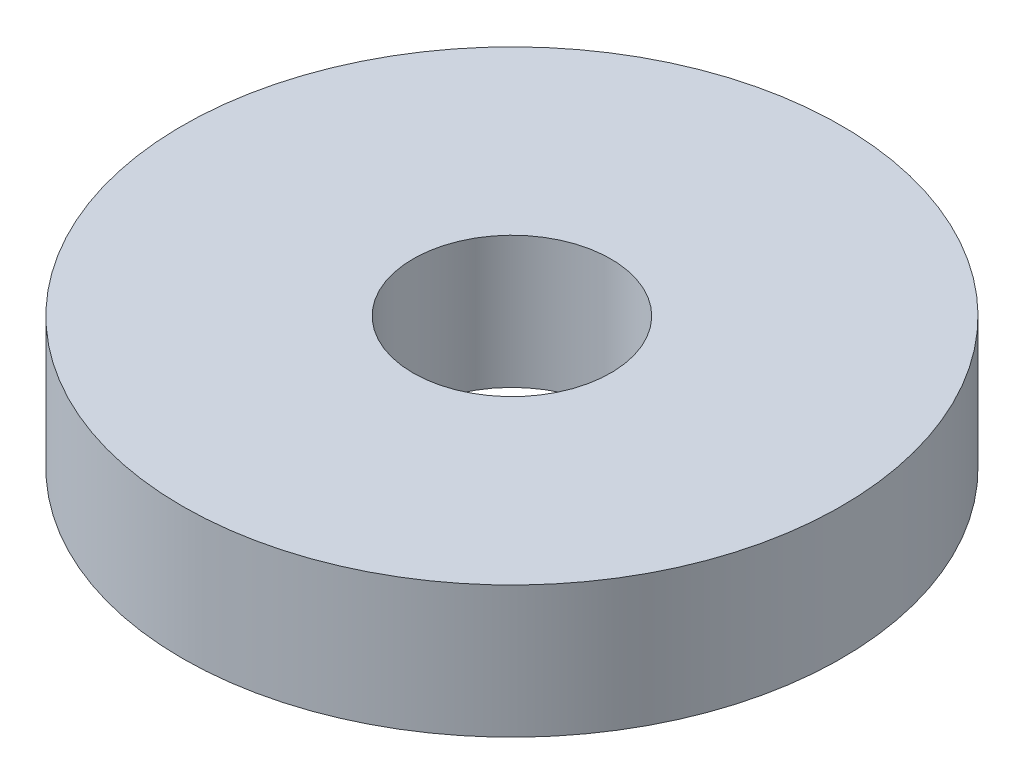
SolidWorks part; units mm, degrees
ref_plane "前视基准面" through (0, 0, 0) normal (0, 0, 1) x (1, 0, 0)
ref_plane "上视基准面" through (0, 0, 0) normal (0, 1, 0) x (1, 0, 0)
ref_plane "右视基准面" through (0, 0, 0) normal (1, 0, 0) x (0, 0, -1)
other "Configuration Table"
sketch "草图1" plane through (0, 0, 0) normal (0, 1, 0) x (1, 0, 0)
  circle A0 centre (0, 0) radius 3
  circle A1 centre (0, 0) radius 10
  dimension "D1" = 6
  dimension "D2" = 20
extrude "凸台-拉伸1" add sketch "草图1" along normal blind 4
